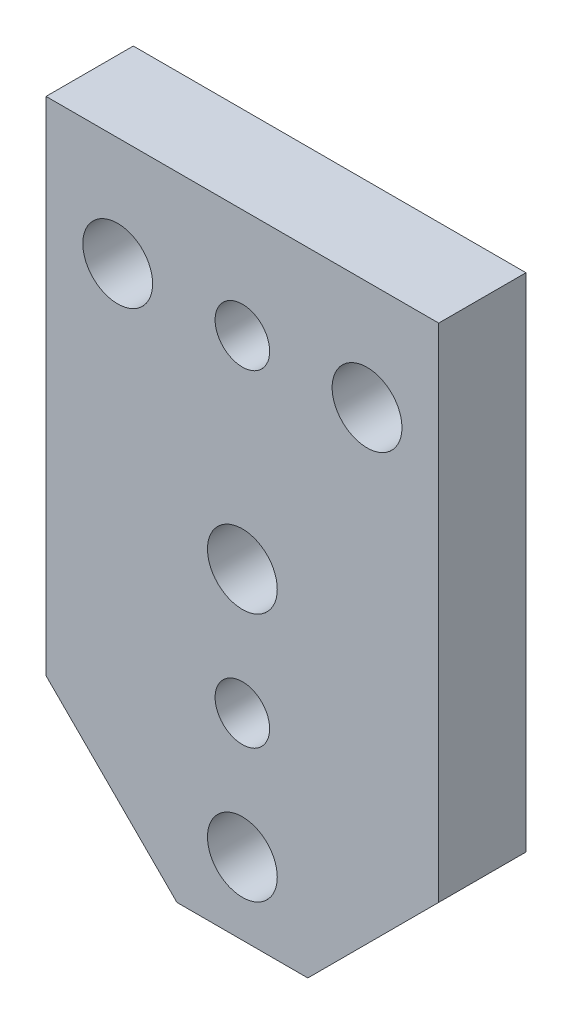
SolidWorks part; units mm, degrees
material "1060 Alloy"
ref_plane "Front Plane" through (0, 0, 0) normal (0, 0, 1) x (1, 0, 0)
ref_plane "Top Plane" through (0, 0, 0) normal (0, 1, 0) x (1, 0, 0)
ref_plane "Right Plane" through (0, 0, 0) normal (1, 0, 0) x (0, 0, -1)
sketch "Sketch1" plane through (0, 0, 0) normal (0, 0, 1) x (1, 0, 0)
  line L1 (-9, -5) -> (9, -5)
  line L2 (-9, -5) -> (-9, 5)
  line L3 (-9, 5) -> (9, 5)
  line L4 (9, -5) -> (9, 5)
  line L5 (-9, -5) -> (9, 5) construction
  line L6 (-9, 5) -> (9, -5) construction
  point P0 (0, 0)
  dimension "D1" = 10
  dimension "D2" = 18
extrude "Boss-Extrude1" add sketch "Sketch1" along normal mid plane 4
sketch "Sketch2" plane through (0, 0, 0) normal (0, 0, 1) x (1, 0, 0)
  line L0 (-9, -5) -> (9, -5) construction
  line L1 (9, -24) -> (-9, -24)
  line L2 (9, -24) -> (9, -5)
  line L3 (9, -5) -> (-9, -5)
  line L4 (-9, -24) -> (-9, -5)
  line L5 (9, -24) -> (-9, -5) construction
  line L6 (9, -5) -> (-9, -24) construction
  line L7 (0, -14.5) -> (0, 0) construction
  point P0 (0, -14.5)
  dimension "D1" = 19
extrude "Boss-Extrude2" add sketch "Sketch2" along normal mid plane 4
hole_wizard "M3 Clearance Hole1" positions "Sketch3" profile "Sketch4" hole size "M3" standard "ISO" end condition through all
sketch "Sketch3" plane through (0, 0, 2) normal (0, 0, -1) x (-1, 0, 0)
  point P0 (0, -9.268)
  point P3 (0, -20.698)
  point P7 (-5.715, 0.0028)
  point P10 (5.715, 0.0028)
sketch "Sketch4" plane through (0, -9.268, 2) normal (1, 0, 0) x (0, -1, 0)
  line L0 (0, 0) -> (0, 4)
  line L1 (0, 4) -> (1.6, 4)
  line L2 (1.6, 4) -> (1.6, 0)
  line L5 (1.6, 0) -> (0, 0)
  line L11 (0, -6.35) -> (0, 107.95) construction
  dimension "Thru Hole Dia." = 3.2
  dimension "Thru Hole Depth" = 4
chamfer "Chamfer1" distance 6 angle 45 2 edges at (-9, -24, 0) (9, -24, 0)
hole_wizard "M3 Tapped Hole1" positions "Sketch5" profile "Sketch6" tap size "M3" standard "ISO" end condition through all
sketch "Sketch5" plane through (0, 0, 2) normal (0, 0, 1) x (1, 0, 0)
  line L0 (-5.715, 0.0028) -> (5.715, 0.0028) construction
  line L2 (0, -20.698) -> (0, -9.268) construction
  point P0 (0, -14.983)
  point P2 (0, 0.0028)
sketch "Sketch6" plane through (0, -14.983, 2) normal (1, 0, 0) x (0, -1, 0)
  line L0 (0, 0) -> (0, 4)
  line L1 (0, 4) -> (1.25, 4)
  line L2 (1.25, 4) -> (1.25, 0)
  line L5 (1.25, 0) -> (0, 0)
  line L11 (0, -6.35) -> (0, 107.95) construction
  dimension "Thru Tap Drill Dia." = 2.5
  dimension "Thru Tap Drill Depth" = 4
cosmetic thread "Hole Thread1" parameters "D2"=3
cosmetic thread "Hole Thread2" parameters "D2"=3
